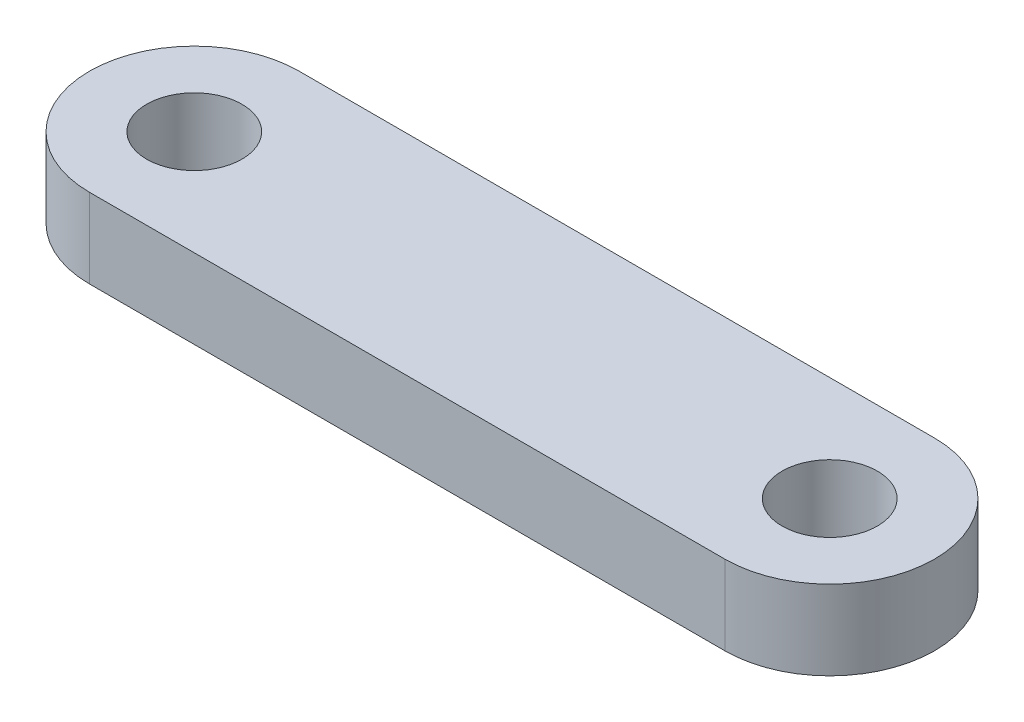
SolidWorks part; units mm, degrees
ref_plane "Front Plane" through (0, 0, 0) normal (0, 0, 1) x (1, 0, 0)
ref_plane "Top Plane" through (0, 0, 0) normal (0, 1, 0) x (1, 0, 0)
ref_plane "Right Plane" through (0, 0, 0) normal (1, 0, 0) x (0, 0, -1)
sketch "Sketch1" plane through (0, 0, 0) normal (0, 1, 0) x (1, 0, 0)
  line L0 (0, 0) -> (101.6, 0)
  line L1 (0, 0) -> (101.6, 0) construction
  line L2 (0, 16.764) -> (101.6, 16.764)
  line L3 (0, -16.764) -> (101.6, -16.764)
  arc A0 (0, 16.764) -> (0, -16.764) centre (0, 0) ccw
  arc A1 (101.6, -16.764) -> (101.6, 16.764) centre (101.6, 0) ccw
  circle A2 centre (0, 0) radius 7.62
  circle A3 centre (101.6, 0) radius 7.62
  point P3 (50.8, 0)
  dimension "D2" = 16.764
  dimension "D1" = 101.6
extrude "Boss-Extrude1" add sketch "Sketch1" along normal blind 12.7
